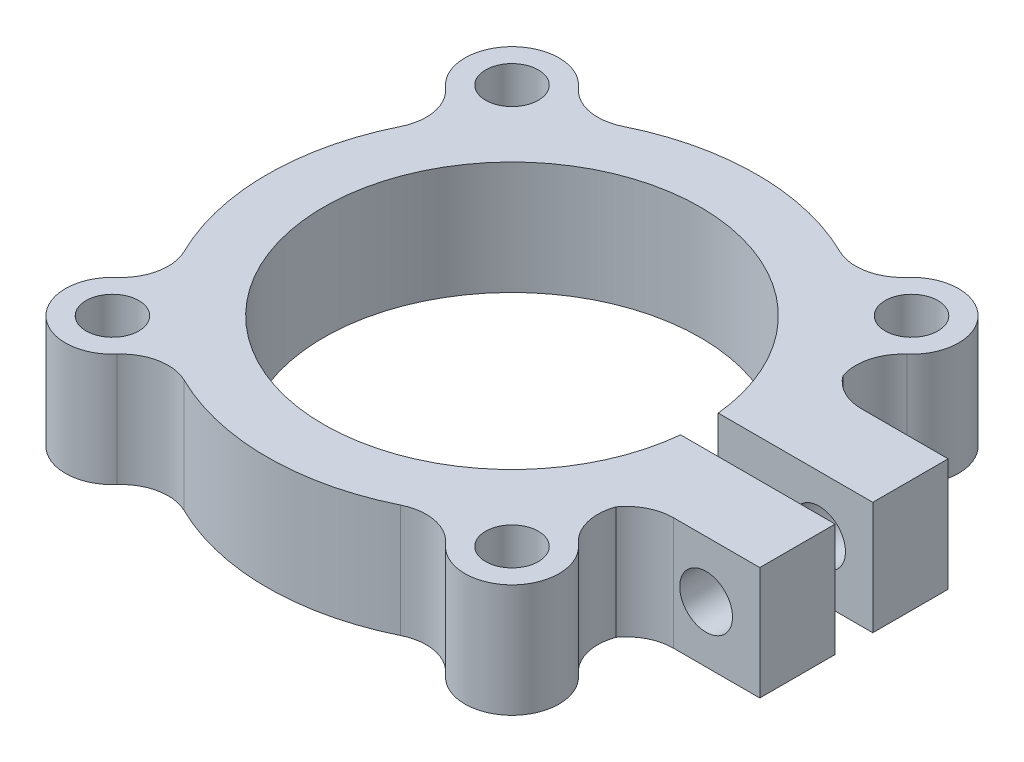
SolidWorks part; units mm, degrees
ref_plane "Front Plane" through (0, 0, 0) normal (0, 0, 1) x (1, 0, 0)
ref_plane "Top Plane" through (0, 0, 0) normal (0, 1, 0) x (1, 0, 0)
ref_plane "Right Plane" through (0, 0, 0) normal (1, 0, 0) x (0, 0, -1)
ref_plane "Plane1" through (0, 7.62, 0) normal (0, 1, 0) x (1, 0, 0)
sketch "Sketch1" plane through (0, 7.62, 0) normal (0, 1, 0) x (1, 0, 0)
  line L0 (23.058, -6.35) -> (23.058, 6.35)
  line L1 (23.058, 6.35) -> (17.2271, 6.35)
  line L2 (17.2271, -6.35) -> (23.058, -6.35)
  arc A0 (17.2271, 6.35) -> (14.6595, 7.6574) centre (17.2271, 9.525) cw
  arc A1 (14.6595, 7.6574) -> (15.5648, 11.0841) centre (17.6592, 8.6979) cw
  arc A2 (15.5648, 11.0841) -> (11.0841, 15.5648) centre (13.4704, 13.4704) ccw
  arc A3 (11.0841, 15.5648) -> (7.295, 14.8109) centre (8.6979, 17.6592) cw
  arc A4 (7.295, 14.8109) -> (-7.295, 14.8109) centre (0, 0) ccw
  arc A5 (-7.295, 14.8109) -> (-11.0841, 15.5648) centre (-8.6979, 17.6592) cw
  arc A6 (-11.0841, 15.5648) -> (-15.5648, 11.0841) centre (-13.4704, 13.4704) ccw
  arc A7 (-15.5648, 11.0841) -> (-14.8109, 7.295) centre (-17.6592, 8.6979) cw
  arc A8 (-14.8109, 7.295) -> (-14.8109, -7.295) centre (0, 0) ccw
  arc A9 (-14.8109, -7.295) -> (-15.5648, -11.0841) centre (-17.6592, -8.6979) cw
  arc A10 (-15.5648, -11.0841) -> (-11.0841, -15.5648) centre (-13.4704, -13.4704) ccw
  arc A11 (-11.0841, -15.5648) -> (-7.295, -14.8109) centre (-8.6979, -17.6592) cw
  arc A12 (-7.295, -14.8109) -> (7.295, -14.8109) centre (0, 0) ccw
  arc A13 (7.295, -14.8109) -> (11.0841, -15.5648) centre (8.6979, -17.6592) cw
  arc A14 (11.0841, -15.5648) -> (15.5648, -11.0841) centre (13.4704, -13.4704) ccw
  arc A15 (15.5648, -11.0841) -> (14.6595, -7.6574) centre (17.6592, -8.6979) cw
  arc A16 (14.6595, -7.6574) -> (17.2271, -6.35) centre (17.2271, -9.525) cw
extrude "Boss-Extrude1" add sketch "Sketch1" against normal blind 7.62
sketch "Sketch2" plane through (0, 0, 0) normal (0, -1, 0) x (1, 0, 0)
  line L0 (23.058, -1.27) -> (23.058, 1.27)
  line L1 (23.058, 1.27) -> (12.6363, 1.27)
  line L2 (12.6363, -1.27) -> (23.058, -1.27)
  arc A0 (12.6363, 1.27) -> (12.6363, -1.27) centre (0, 0) cw
extrude "Cut-Extrude1" cut sketch "Sketch2" against normal through all
sketch "Sketch3" plane through (0, 0, 0) normal (0, 0, 1) x (1, 0, 0)
  line L0 (12.7, 7.62) -> (0, 7.62)
  line L1 (0, 7.62) -> (0, 0)
  line L2 (0, 0) -> (12.7, 0)
  line L3 (12.7, 0) -> (12.7, 7.62)
  line L4 (0, 7.62) -> (0, 0) construction
revolve "Cut-Revolve1" cut sketch "Sketch3" angle 360 about L4
hole_wizard "#5 Clearance Hole1" positions "Sketch5" profile "Sketch4" hole size "#5" standard "ANSI Inch"
sketch "Sketch5" plane through (0, 7.62, 0) normal (0, 1, 0) x (1, 0, 0)
  point P0 (13.4704, -13.4704)
  point P1 (-13.4704, -13.4704)
  point P2 (-13.4704, 13.4704)
  point P3 (13.4704, 13.4704)
sketch "Sketch4" plane through (13.4704, 7.62, 13.4704) normal (1, 0, 0) x (0, 0, 1)
  line L0 (0, 0) -> (0, 7.62)
  line L1 (0, 7.62) -> (1.778, 7.62)
  line L2 (1.778, 7.62) -> (1.778, 0)
  line L5 (1.778, 0) -> (0, 0)
  line L11 (0, -6.35) -> (0, 107.95) construction
  dimension "Thru Hole Dia." = 3.556
  dimension "Thru Hole Depth" = 7.62
hole_wizard "#36 (0.1065) Diameter Hole1" positions "Sketch7" profile "Sketch6" hole size "#36" standard "ANSI Inch"
sketch "Sketch7" plane through (0, 0, -6.35) normal (0, 0, -1) x (-1, 0, 0)
  point P0 (-19.4388, 3.81)
sketch "Sketch6" plane through (19.4388, 3.81, -6.35) normal (1, 0, 0) x (0, 1, 0)
  line L0 (0, 0) -> (0, 5.08)
  line L1 (0, 5.08) -> (1.3525, 5.08)
  line L2 (1.3525, 5.08) -> (1.3525, 0)
  line L5 (1.3525, 0) -> (0, 0)
  line L11 (0, -6.35) -> (0, 107.95) construction
  dimension "Thru Hole Dia." = 2.7051
  dimension "Thru Hole Depth" = 5.08
hole_wizard "#5 Clearance Hole2" positions "Sketch9" profile "Sketch8" hole size "#5" standard "ANSI Inch"
sketch "Sketch9" plane through (0, 0, 6.35) normal (0, 0, 1) x (1, 0, 0)
  point P0 (19.4388, 3.81)
sketch "Sketch8" plane through (19.4388, 3.81, 6.35) normal (1, 0, 0) x (0, -1, 0)
  line L0 (0, 0) -> (0, 22.9954)
  line L1 (0, 22.9954) -> (1.778, 22.9954)
  line L2 (1.778, 22.9954) -> (1.778, 0)
  line L5 (1.778, 0) -> (0, 0)
  line L11 (0, -6.35) -> (0, 107.95) construction
  dimension "Thru Hole Dia." = 3.556
  dimension "Thru Hole Depth" = 22.9954
